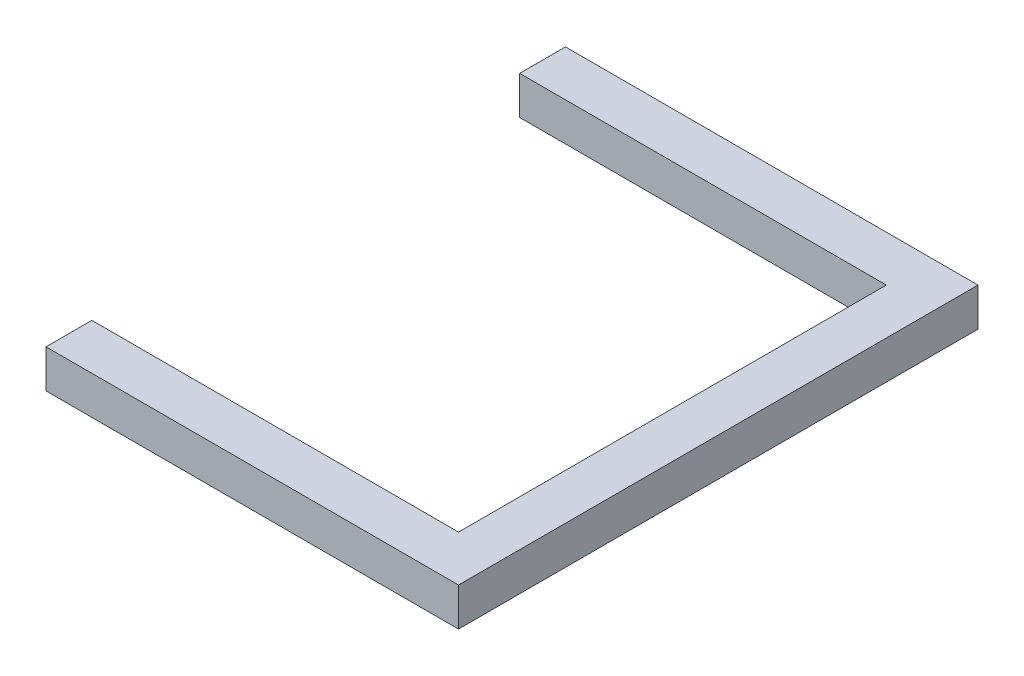
SolidWorks part; units mm, degrees
ref_plane "Front Plane" through (0, 0, 0) normal (0, 0, 1) x (1, 0, 0)
ref_plane "Top Plane" through (0, 0, 0) normal (0, 1, 0) x (1, 0, 0)
ref_plane "Right Plane" through (0, 0, 0) normal (1, 0, 0) x (0, 0, -1)
sketch "Sketch1" plane through (0, 0, 0) normal (0, 1, 0) x (1, 0, 0)
  line L0 (0, 14) -> (0, -14)
  line L1 (0, 14) -> (-24, 14)
  line L2 (0, -14) -> (-24, -14)
  line L3 (3, 17) -> (-24, 17)
  line L4 (3, 17) -> (3, -17)
  line L5 (3, -17) -> (-24, -17)
  line L6 (-24, 17) -> (-24, 14)
  line L7 (-24, -14) -> (-24, -17)
  point P4 (0, 0)
  dimension "D1" = 28
  dimension "D2" = 24
  dimension "D3" = 3
extrude "Boss-Extrude1" add sketch "Sketch1" along normal blind 2.5
